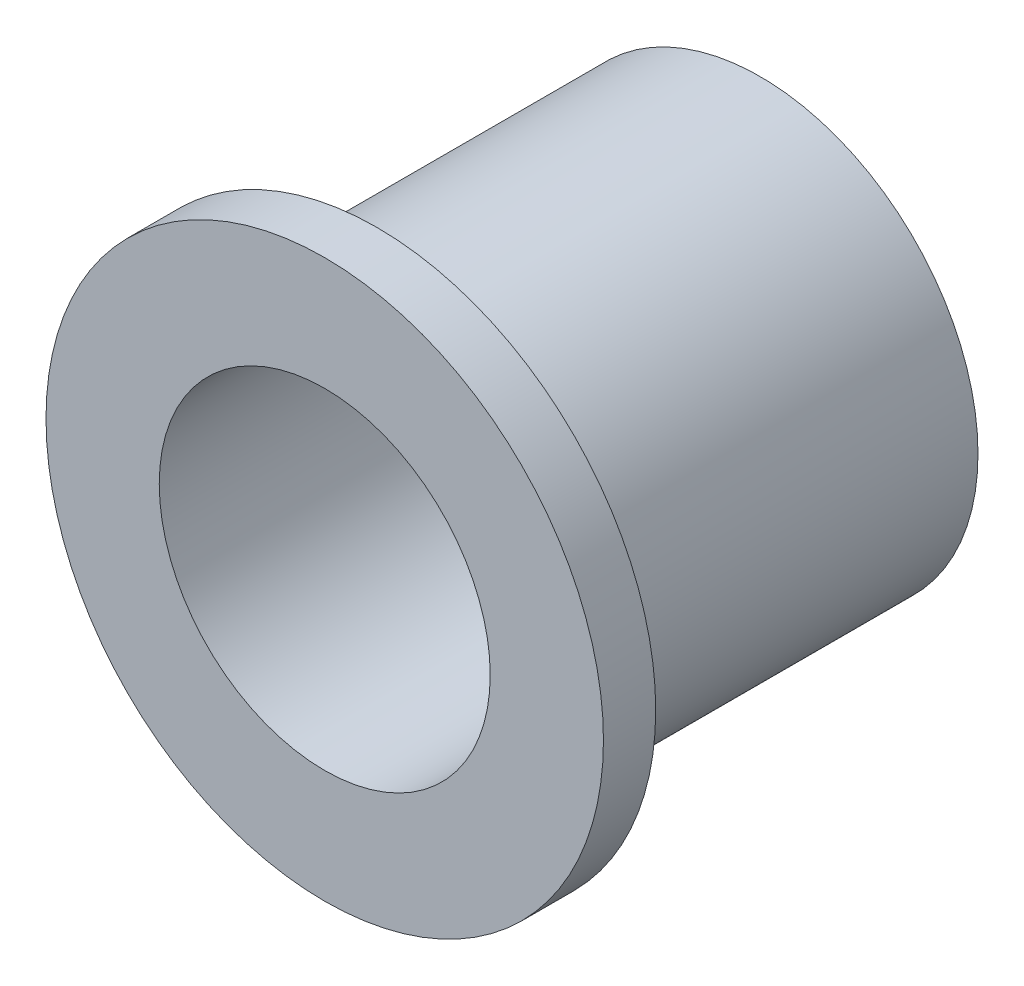
SolidWorks part; units mm, degrees
ref_plane "Alzado" through (0, 0, 0) normal (0, 0, 1) x (1, 0, 0)
ref_plane "Planta" through (0, 0, 0) normal (0, 1, 0) x (1, 0, 0)
ref_plane "Vista lateral" through (0, 0, 0) normal (1, 0, 0) x (0, 0, -1)
sketch "Croquis1" plane through (0, 0, 0) normal (0, 0, 1) x (1, 0, 0)
  circle A0 centre (0, 0) radius 12.5
  dimension "D1" = 25
extrude "Saliente-Extruir1" add sketch "Croquis1" along normal blind 22
sketch "Croquis2" plane through (0, 0, 22) normal (0, 0, 1) x (1, 0, 0)
  circle A0 centre (0, 0) radius 16
  dimension "D1" = 32
extrude "Saliente-Extruir2" add sketch "Croquis2" along normal blind 3
sketch "Croquis3" plane through (0, 0, 25) normal (0, 0, 1) x (1, 0, 0)
  circle A0 centre (0, 0) radius 9.5
  dimension "D1" = 19
extrude "Cortar-Extruir1" cut sketch "Croquis3" against normal through all
